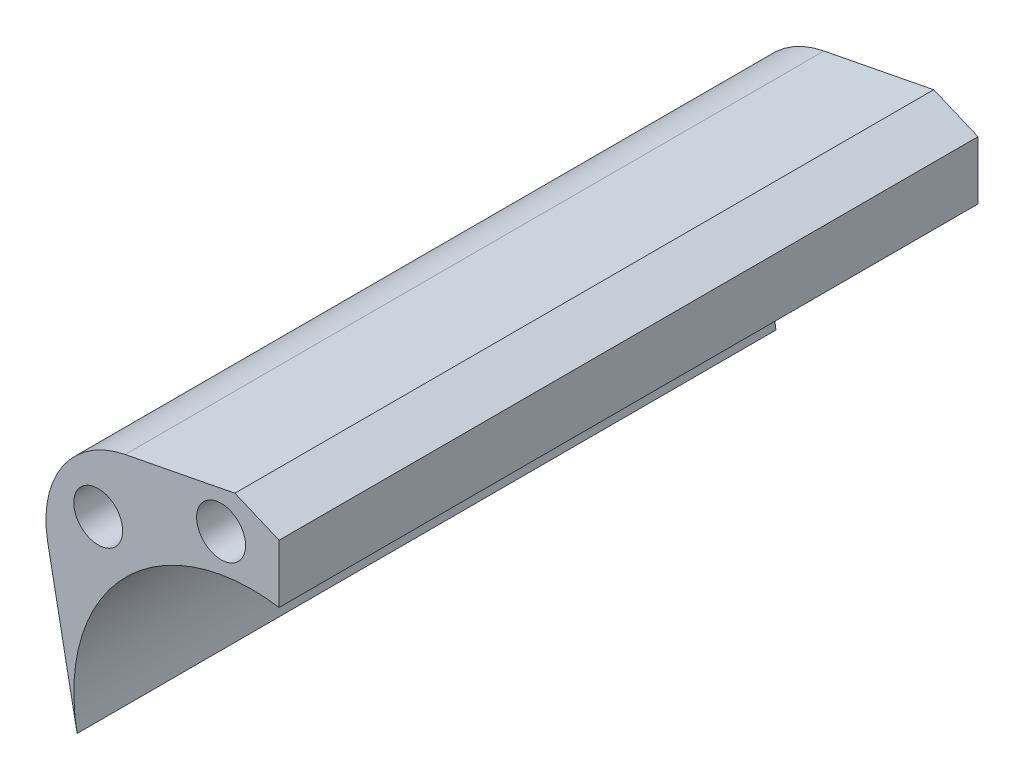
SolidWorks part; units mm, degrees
ref_plane "Front Plane" through (0, 0, 0) normal (0, 0, 1) x (1, 0, 0)
ref_plane "Top Plane" through (0, 0, 0) normal (0, 1, 0) x (1, 0, 0)
ref_plane "Right Plane" through (0, 0, 0) normal (1, 0, 0) x (0, 0, -1)
sketch "Sketch1" plane through (0, 0, 0) normal (0, 0, 1) x (1, 0, 0)
  line L4 (17.9494, 2.9944) -> (25.7485, 7.4859)
  line L5 (7.786, 14.3196) -> (-1.2277, 18.0985)
  line L6 (-1.2277, 18.0985) -> (-9.0806, 16.5712)
  line L7 (-14.6155, 8.3636) -> (-12.5155, -2.4341)
  line L9 (1.9391, 16.7708) -> (-1.2277, 18.0985)
  line L10 (-1.2277, 18.0985) -> (-9.0806, 16.5712)
  line L11 (-14.6155, 8.3636) -> (-12.5155, -2.4341)
  line L13 (1.9391, 16.7708) -> (1.9391, 12.6017)
  line L19 (22.3334, 16.8847) -> (7.786, 14.3196)
  line L43 (12.75, 0) -> (11.8356, -5.9299)
  line L44 (12.75, 0) -> (11.8356, -5.9299)
  circle A0 centre (-11.0059, 11.7506) radius 1.75 construction
  circle A1 centre (-11.0059, 11.7506) radius 1.75
  arc A2 (12.75, 0) -> (-12.5155, -2.4341) centre (0, 0) ccw
  arc A3 (-9.0806, 16.5712) -> (-14.6155, 8.3636) centre (-7.7442, 9.7) ccw
  arc A4 (1.9391, 12.6017) -> (-12.5155, -2.4341) centre (0, 0) ccw
  arc A5 (-9.0806, 16.5712) -> (-14.6155, 8.3636) centre (-7.7442, 9.7) ccw
  circle A6 centre (-2.214, 15.2348) radius 1.75 construction
  circle A7 centre (-2.214, 15.2348) radius 1.75
  arc A14 (25.7485, 7.4859) -> (22.3334, 16.8847) centre (23.215, 11.8852) ccw
  arc A30 (11.8356, -5.9299) -> (17.9494, 2.9944) centre (12.75, 0) ccw
  arc A31 (11.8356, -5.9299) -> (17.9494, 2.9944) centre (12.75, 0) ccw
  dimension "D1" = 0
extrude "Boss-Extrude1" add sketch "Sketch1" along normal blind 50 contours L10 A5 L11 A4 L13 L9 A7 A1
